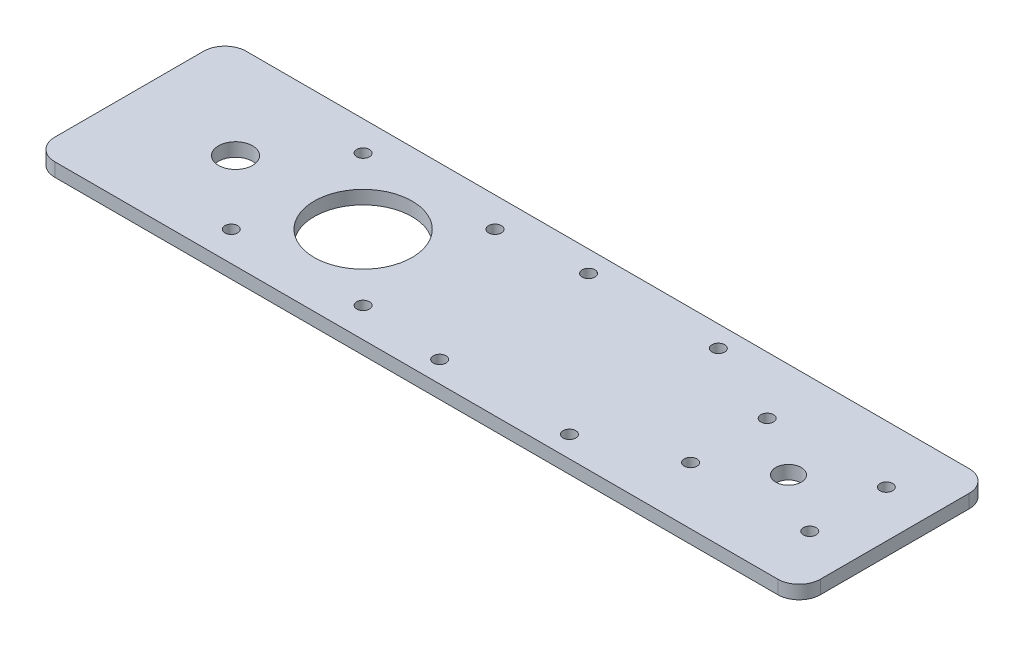
SolidWorks part; units mm, degrees
ref_plane "Front Plane" through (0, 0, 0) normal (0, 0, 1) x (1, 0, 0)
ref_plane "Top Plane" through (0, 0, 0) normal (0, 1, 0) x (1, 0, 0)
ref_plane "Right Plane" through (0, 0, 0) normal (1, 0, 0) x (0, 0, -1)
sketch "Sketch1" plane through (0, 0, 0) normal (0, 1, 0) x (1, 0, 0)
  line L1 (-25, 22.5) -> (155, 22.5)
  line L2 (-25, 22.5) -> (-25, -22.5)
  line L3 (-25, -22.5) -> (155, -22.5)
  line L4 (155, 22.5) -> (155, -22.5)
  point P4 (-25, 0)
  dimension "D1" = 45
  dimension "D2" = 180
  dimension "D3" = 25
extrude "Boss-Extrude1" add sketch "Sketch1" along normal blind 3.175
fillet "Fillet1" radius 5 4 edges at (-25, 1.5875, 22.5) (-25, 1.5875, -22.5) (155, 1.5875, -22.5) (155, 1.5875, 22.5)
sketch "Sketch4" plane through (0, 3.175, 0) normal (0, 1, 0) x (1, 0, 0)
  line L0 (155, 0) -> (-25, 0) construction
  line L1 (155, -17.5) -> (155, 17.5) construction
  line L2 (-25, 17.5) -> (-25, -17.5) construction
  line L3 (130, 22.5) -> (130, -22.5) construction
  line L4 (150, 22.5) -> (-20, 22.5) construction
  line L5 (-20, -22.5) -> (150, -22.5) construction
  circle A0 centre (130, 0) radius 3
  circle A1 centre (116, 9) radius 1.5
  circle A2 centre (144, 9) radius 1.5
  circle A3 centre (144, -9) radius 1.5
  circle A4 centre (116, -9) radius 1.5
  dimension "D1" = 6
  dimension "D5" = 3
  dimension "D2" = 25
  dimension "D3" = 14
  dimension "D4" = 9
extrude "Cut-Extrude1" cut sketch "Sketch4" against normal through all
sketch "Sketch5" plane through (0, 3.175, 0) normal (0, 1, 0) x (1, 0, 0)
  circle A0 centre (0, 0) radius 4
  dimension "D1" = 8
extrude "Cut-Extrude2" cut sketch "Sketch5" against normal through all
sketch "Sketch6" plane through (0, 3.175, 0) normal (0, 1, 0) x (1, 0, 0)
  line L0 (-25, 17.5) -> (-25, -17.5) construction
  line L3 (9, 0) -> (51, 0) construction
  line L4 (30, -21) -> (30, 21) construction
  circle A0 centre (14.5, -15.5) radius 1.5
  circle A1 centre (0, 0) radius 4 construction
  circle A2 centre (14.5, 15.5) radius 1.5
  circle A3 centre (45.5, 15.5) radius 1.5
  circle A4 centre (45.5, -15.5) radius 1.5
  circle A5 centre (30, 0) radius 11.5
  point P7 (-25, 0)
  point P8 (30, 0)
  point P11 (30, 0)
  point P14 (30, 0)
  dimension "D1" = 30
  dimension "D4" = 3
  dimension "D7" = 23
  dimension "D2" = 42
  dimension "D3" = 42
  dimension "D5" = 15.5
  dimension "D6" = 15.5
extrude "Cut-Extrude3" cut sketch "Sketch6" against normal through all
sketch "Sketch10" plane through (0, 3.175, 0) normal (0, 1, 0) x (1, 0, 0)
  line L0 (-25, 0) -> (155, 0) construction
  line L1 (-25, 17.5) -> (-25, -17.5) construction
  line L2 (155, -17.5) -> (155, 17.5) construction
  line L3 (-20, -22.5) -> (150, -22.5) construction
  circle A0 centre (65.5, -17.5) radius 1.5
  circle A1 centre (45.5, -15.5) radius 1.5 construction
  circle A2 centre (96, -17.5) radius 1.5
  circle A3 centre (116, -9) radius 1.5 construction
  circle A4 centre (96, 17.5) radius 1.5
  circle A5 centre (65.5, 17.5) radius 1.5
  dimension "D3" = 3
  dimension "D4" = 20
  dimension "D1" = 20
  dimension "D2" = 5
extrude "Cut-Extrude4" cut sketch "Sketch10" against normal through all
